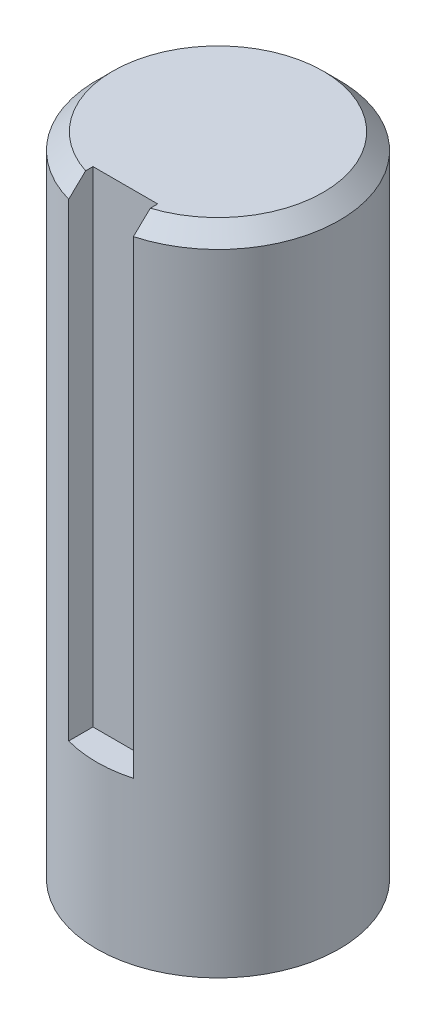
SolidWorks part; units mm, degrees
ref_plane "Front Plane" through (0, 0, 0) normal (1, 0, 0) x (0, 1, 0)
ref_plane "Top Plane" through (0, 0, 0) normal (0, 0, 1) x (0, 1, 0)
ref_plane "Right Plane" through (0, 0, 0) normal (0, 1, 0) x (-1, 0, 0)
sketch "Sketch1" plane through (0, 0, 0) normal (0, 1, 0) x (-1, 0, 0)
  circle A0 centre (0, 0) radius 15
  dimension "D1" = 30
extrude "Boss-Extrude1" add sketch "Sketch1" along normal blind 80
chamfer "Chamfer1" distance 2 angle 45 1 edges at (0, 80, 15)
sketch "Sketch3" plane through (0, 80, 0) normal (0, 1, 0) x (-1, 0, 0)
  line L0 (0, 0) -> (0, 22.5222) construction
  line L2 (-4, 14.4568) -> (-4, 11.4568)
  line L3 (-4, 11.4568) -> (4, 11.4568)
  line L4 (4, 14.4568) -> (4, 11.4568)
  circle A2 centre (0, 0) radius 15 construction
  arc A3 (4, 14.4568) -> (-4, 14.4568) centre (0, 0) ccw
  point P3 (0, 0)
  dimension "D2" = 3
  dimension "D3" = 8
extrude "Cut-Extrude1" cut sketch "Sketch3" against normal blind 60
